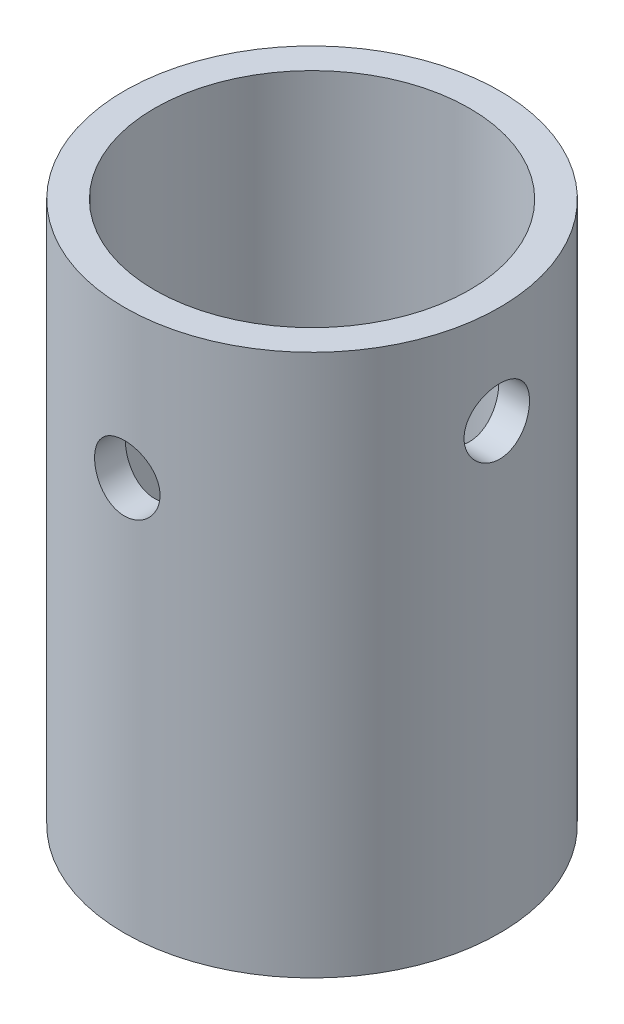
SolidWorks part; units mm, degrees
ref_plane "Front Plane" through (0, 0, 0) normal (0, 0, 1) x (1, 0, 0)
ref_plane "Top Plane" through (0, 0, 0) normal (0, 1, 0) x (1, 0, 0)
ref_plane "Right Plane" through (0, 0, 0) normal (1, 0, 0) x (0, 0, -1)
sketch "Sketch1" plane through (0, 0, 0) normal (0, 1, 0) x (1, 0, 0)
  circle A0 centre (0, 0) radius 24.1681
  dimension "D1" = 48.3362
extrude "Boss-Extrude1" add sketch "Sketch1" against normal blind 69.7992
sketch "Sketch2" plane through (0, 0, 0) normal (0, 1, 0) x (1, 0, 0)
  circle A0 centre (0, 0) radius 20.2819
  dimension "D1" = 40.5638
extrude "Cut-Extrude1" cut sketch "Sketch2" against normal through all
sketch "Sketch3" plane through (0, 0, 0) normal (0, 0, 1) x (1, 0, 0)
  line L0 (20.2819, 0) -> (-20.2819, 0) construction
  line L1 (24.1681, -69.7992) -> (24.1681, 0) construction
  circle A0 centre (0, -19.05) radius 4.2164
  dimension "D1" = 8.4328
  dimension "D2" = 19.05
  dimension "D3" = 24.1681
extrude "Cut-Extrude2" cut sketch "Sketch3" along normal blind 69.7992
sketch "Sketch4" plane through (0, 0, 0) normal (1, 0, 0) x (0, 0, -1)
  line L0 (20.2819, 0) -> (-20.2819, 0) construction
  line L1 (24.1681, -69.7992) -> (24.1681, 0) construction
  circle A0 centre (0, -12.7) radius 4.2164
  dimension "D1" = 8.4328
  dimension "D2" = 12.7
  dimension "D3" = 24.1681
extrude "Cut-Extrude3" cut sketch "Sketch4" along normal blind 69.7992
